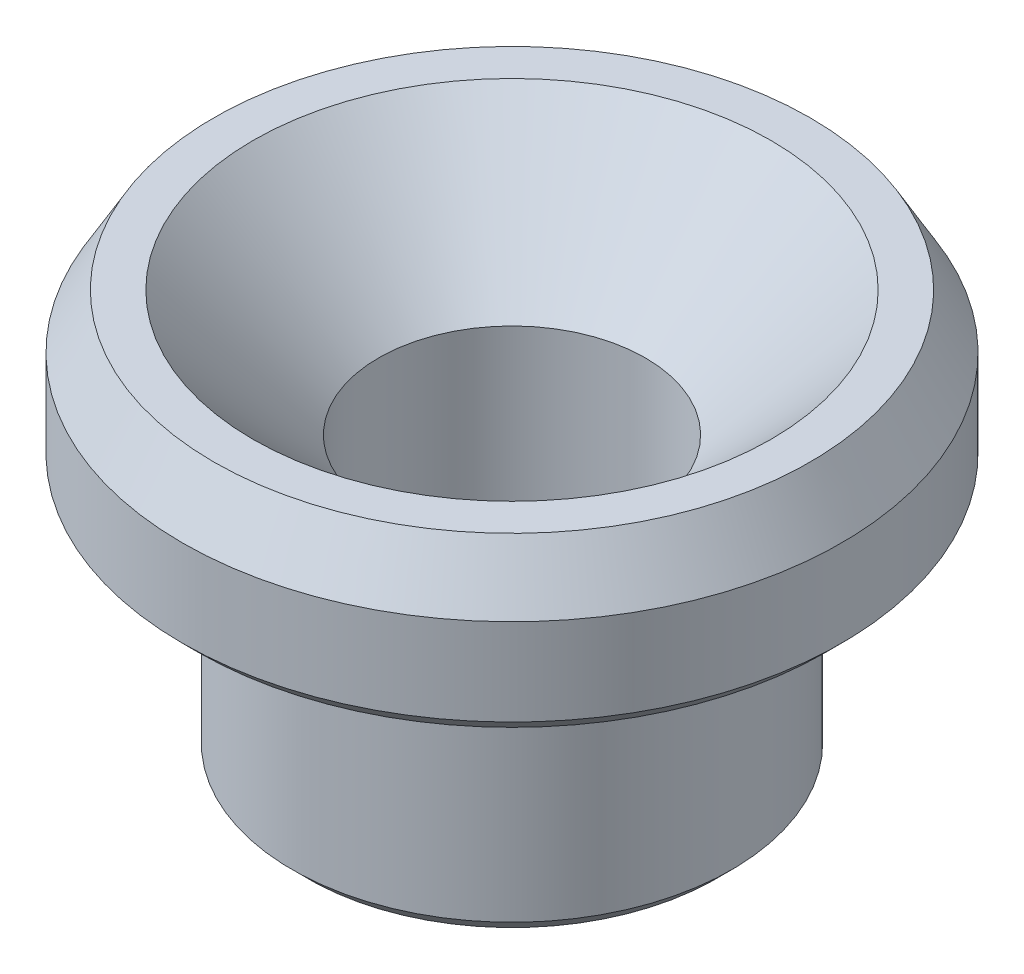
SolidWorks part; units mm, degrees
material "Plain Carbon Steel"
ref_plane "Front Plane" through (0, 0, 0) normal (0, 0, 1) x (1, 0, 0)
ref_plane "Top Plane" through (0, 0, 0) normal (0, 1, 0) x (1, 0, 0)
ref_plane "Right Plane" through (0, 0, 0) normal (1, 0, 0) x (0, 0, -1)
sketch "Sketch1" plane through (0, 0, 0) normal (0, 0, 1) x (1, 0, 0)
  line L0 (0, 0) -> (0, 17.2258) construction
  line L1 (0, 0) -> (12.6996, 0) construction
  line L2 (4.25, 0) -> (4.25, 9)
  line L3 (4.25, 9) -> (8.25, 13)
  line L4 (8.25, 13) -> (10.5, 13)
  line L6 (10.5, 13) -> (10.5, 8)
  line L7 (10.5, 8) -> (7, 8)
  line L8 (7, 8) -> (7, 0)
  line L9 (7, 0) -> (4.25, 0)
  line L10 (4.25, 9) -> (4.25, 6.986) construction
  point P6 (0, 0)
  point P15 (0, 0)
  dimension "D1" = 8.5
  dimension "D2" = 14
  dimension "D3" = 21
  dimension "D4" = 45
  dimension "D5" = 8
  dimension "D6" = 9
  dimension "D7" = 13
revolve "Revolve1" add sketch "Sketch1" angle 360 about L0
chamfer "Chamfer1" distance 1 angle 60 1 edges at (0, 13, -10.5)
chamfer "Chamfer2" distance 0.5 2 edges at (0, 0, -7) (0, 8, -10.5)
